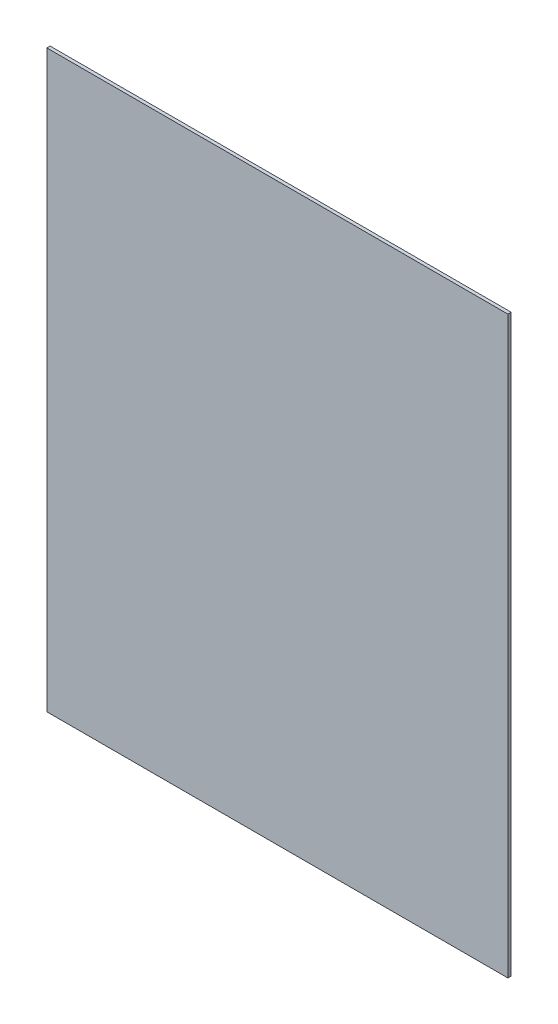
SolidWorks part; units mm, degrees
ref_plane "Front" through (0, 0, 0) normal (0, 0, 1) x (1, 0, 0)
ref_plane "Top" through (0, 0, 0) normal (0, 1, 0) x (1, 0, 0)
ref_plane "Right" through (0, 0, 0) normal (1, 0, 0) x (0, 0, -1)
sketch "Sketch1" plane through (0, 0, 0) normal (0, 0, 1) x (1, 0, 0)
  line L1 (0, 0) -> (448.1322, 0)
  line L2 (0, 0) -> (0, 558.8)
  line L3 (0, 558.8) -> (448.1322, 558.8)
  line L4 (448.1322, 0) -> (448.1322, 558.8)
  dimension "D1" = 558.8
  dimension "D2" = 448.1322
extrude "Boss-Extrude1" add sketch "Sketch1" along normal blind 3.175
